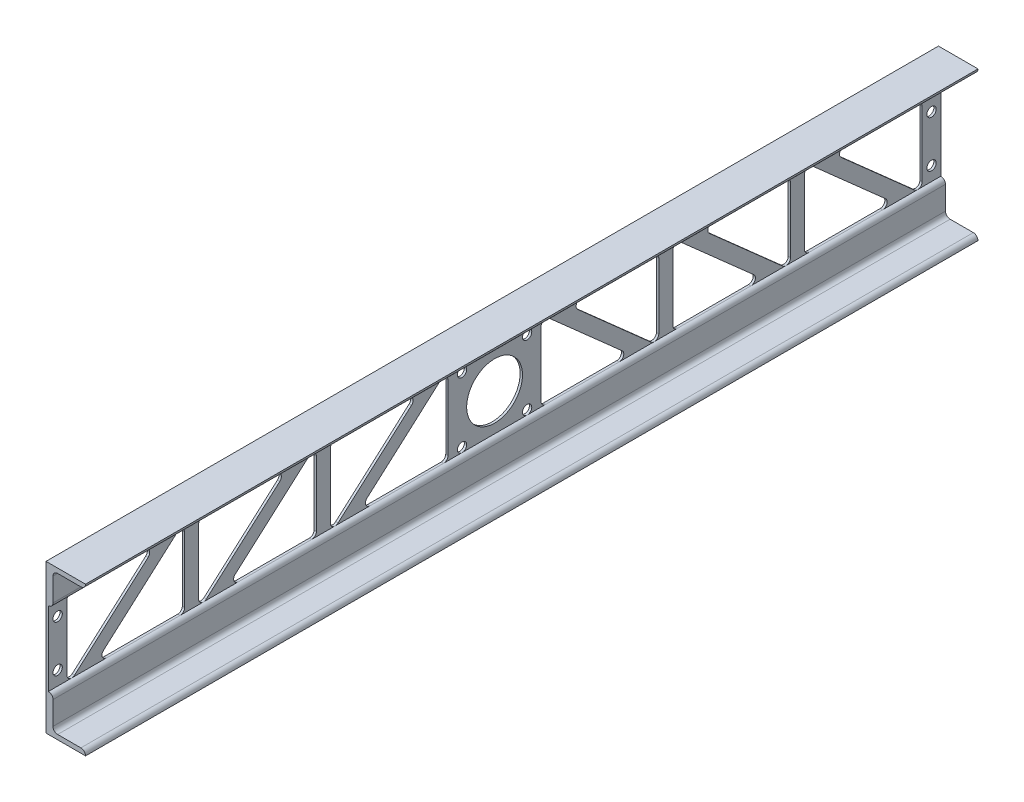
SolidWorks part; units mm, degrees
material "6061 Alloy"
ref_plane "Front Plane" through (0, 0, 0) normal (0, 0, 1) x (1, 0, 0)
ref_plane "Top Plane" through (0, 0, 0) normal (0, 1, 0) x (1, 0, 0)
ref_plane "Right Plane" through (0, 0, 0) normal (1, 0, 0) x (0, 0, -1)
sketch "Sketch1" plane through (0, 0, 0) normal (0, 0, 1) x (1, 0, 0)
  line L1 (0, 0) -> (1.6002, 0)
  line L2 (0, 0) -> (0, 101.6)
  line L3 (0, 101.6) -> (1.6002, 101.6)
  line L4 (1.6002, 0) -> (1.6002, 101.6)
  dimension "D1" = 101.6
  dimension "D2" = 1.6002
extrude "Boss-Extrude1" add sketch "Sketch1" along normal mid plane 609.6
sketch "Sketch2" plane through (0, 0, 0) normal (0, 0, 1) x (1, 0, 0)
  line L0 (27.0002, 101.6) -> (1.6002, 101.6)
  line L1 (1.6002, 101.6) -> (1.6002, 76.2)
  line L2 (4.7752, 79.375) -> (4.7752, 95.25)
  line L3 (7.9502, 98.425) -> (23.8252, 98.425)
  line L4 (1.6002, 50.8) -> (27.0002, 50.8) construction
  line L5 (1.6002, 0) -> (1.6002, 101.6) construction
  line L6 (7.9502, 3.175) -> (23.8252, 3.175)
  line L7 (4.7752, 22.225) -> (4.7752, 6.35)
  line L8 (1.6002, 0) -> (1.6002, 25.4)
  line L9 (27.0002, 0) -> (1.6002, 0)
  arc A0 (1.6002, 76.2) -> (4.7752, 79.375) centre (1.6002, 79.375) ccw
  arc A1 (27.0002, 101.6) -> (23.8252, 98.425) centre (23.8252, 101.6) cw
  arc A2 (4.7752, 95.25) -> (7.9502, 98.425) centre (7.9502, 95.25) cw
  arc A3 (4.7752, 6.35) -> (7.9502, 3.175) centre (7.9502, 6.35) ccw
  arc A4 (27.0002, 0) -> (23.8252, 3.175) centre (23.8252, 0) ccw
  arc A5 (1.6002, 25.4) -> (4.7752, 22.225) centre (1.6002, 22.225) cw
  dimension "D1" = 3.175
  dimension "D2" = 25.4
extrude "Boss-Extrude2" add sketch "Sketch2" along normal mid plane 609.6
sketch "Sketch3" plane through (1.6002, 0, 0) normal (1, 0, 0) x (0, 0, -1)
  line L0 (0, 25.4) -> (0, 76.2) construction
  line L1 (-304.8, 25.4) -> (304.8, 25.4) construction
  line L2 (-304.8, 76.2) -> (304.8, 76.2) construction
  line L3 (-292.1, 73.025) -> (-292.1, 28.575)
  line L4 (-288.925, 76.2) -> (-238.7751, 76.2)
  line L5 (-236.6691, 70.649) -> (-286.819, 26.199)
  line L6 (-304.8, 25.4) -> (-304.8, 76.2) construction
  line L7 (-264.9916, 25.4) -> (-214.8417, 25.4)
  line L8 (-211.6667, 28.575) -> (-211.6667, 73.025)
  line L9 (-216.9476, 75.401) -> (-267.0976, 30.951)
  line L10 (-261.7441, 48.424) -> (-255.4261, 41.2959) construction
  line L11 (-211.6667, 50.8) -> (-202.1417, 50.8) construction
  line L12 (-202.1417, 73.025) -> (-202.1417, 28.575)
  line L13 (-198.9667, 76.2) -> (-148.8167, 76.2)
  line L14 (-146.7108, 70.649) -> (-196.8607, 26.199)
  line L15 (-126.9893, 75.401) -> (-177.1392, 30.951)
  line L16 (-121.7083, 28.575) -> (-121.7083, 73.025)
  line L17 (-175.0333, 25.4) -> (-124.8833, 25.4)
  line L18 (-171.7857, 48.424) -> (-165.4678, 41.2959) construction
  line L19 (-121.7083, 50.8) -> (-112.1833, 50.8) construction
  line L20 (-112.1833, 73.025) -> (-112.1833, 28.575)
  line L21 (-109.0083, 76.2) -> (-58.8584, 76.2)
  line L22 (-56.7524, 70.649) -> (-106.9024, 26.199)
  line L23 (-37.031, 75.401) -> (-87.1809, 30.951)
  line L24 (-31.75, 28.575) -> (-31.75, 73.025)
  line L25 (-85.0749, 25.4) -> (-34.925, 25.4)
  line L26 (-81.8274, 48.424) -> (-75.5095, 41.2959) construction
  line L27 (0, 50.8) -> (-31.75, 50.8) construction
  line L28 (-31.75, 50.8) -> (-22.225, 50.8) construction
  line L29 (81.8274, 48.424) -> (75.5095, 41.2959) construction
  line L30 (121.7083, 50.8) -> (112.1833, 50.8) construction
  line L31 (171.7857, 48.424) -> (165.4678, 41.2959) construction
  line L32 (211.6667, 50.8) -> (202.1417, 50.8) construction
  line L33 (261.7441, 48.424) -> (255.4261, 41.2959) construction
  line L34 (85.0749, 25.4) -> (34.925, 25.4)
  line L35 (31.75, 28.575) -> (31.75, 73.025)
  line L36 (37.031, 75.401) -> (87.1809, 30.951)
  line L37 (56.7524, 70.649) -> (106.9024, 26.199)
  line L38 (109.0083, 76.2) -> (58.8584, 76.2)
  line L39 (112.1833, 73.025) -> (112.1833, 28.575)
  line L40 (175.0333, 25.4) -> (124.8833, 25.4)
  line L41 (121.7083, 28.575) -> (121.7083, 73.025)
  line L42 (126.9893, 75.401) -> (177.1392, 30.951)
  line L43 (146.7108, 70.649) -> (196.8607, 26.199)
  line L44 (198.9667, 76.2) -> (148.8167, 76.2)
  line L45 (202.1417, 73.025) -> (202.1417, 28.575)
  line L46 (216.9476, 75.401) -> (267.0976, 30.951)
  line L47 (211.6667, 28.575) -> (211.6667, 73.025)
  line L48 (264.9916, 25.4) -> (214.8417, 25.4)
  line L49 (236.6691, 70.649) -> (286.819, 26.199)
  line L50 (288.925, 76.2) -> (238.7751, 76.2)
  line L51 (292.1, 73.025) -> (292.1, 28.575)
  circle A0 centre (0, 50.8) radius 19.05
  arc A1 (-292.1, 28.575) -> (-286.819, 26.199) centre (-288.925, 28.575) ccw
  arc A2 (-238.7751, 76.2) -> (-236.6691, 70.649) centre (-238.7751, 73.025) cw
  arc A3 (-292.1, 73.025) -> (-288.925, 76.2) centre (-288.925, 73.025) cw
  arc A4 (-264.9916, 25.4) -> (-267.0976, 30.951) centre (-264.9916, 28.575) cw
  arc A5 (-214.8417, 25.4) -> (-211.6667, 28.575) centre (-214.8417, 28.575) ccw
  arc A6 (-211.6667, 73.025) -> (-216.9476, 75.401) centre (-214.8417, 73.025) ccw
  arc A7 (-202.1417, 73.025) -> (-198.9667, 76.2) centre (-198.9667, 73.025) cw
  arc A8 (-148.8167, 76.2) -> (-146.7108, 70.649) centre (-148.8167, 73.025) cw
  arc A9 (-202.1417, 28.575) -> (-196.8607, 26.199) centre (-198.9667, 28.575) ccw
  arc A10 (-175.0333, 25.4) -> (-177.1392, 30.951) centre (-175.0333, 28.575) cw
  arc A11 (-121.7083, 73.025) -> (-126.9893, 75.401) centre (-124.8833, 73.025) ccw
  arc A12 (-124.8833, 25.4) -> (-121.7083, 28.575) centre (-124.8833, 28.575) ccw
  arc A13 (-112.1833, 73.025) -> (-109.0083, 76.2) centre (-109.0083, 73.025) cw
  arc A14 (-58.8584, 76.2) -> (-56.7524, 70.649) centre (-58.8584, 73.025) cw
  arc A15 (-112.1833, 28.575) -> (-106.9024, 26.199) centre (-109.0083, 28.575) ccw
  arc A16 (-85.0749, 25.4) -> (-87.1809, 30.951) centre (-85.0749, 28.575) cw
  arc A17 (-31.75, 73.025) -> (-37.031, 75.401) centre (-34.925, 73.025) ccw
  arc A18 (-34.925, 25.4) -> (-31.75, 28.575) centre (-34.925, 28.575) ccw
  arc A19 (34.925, 25.4) -> (31.75, 28.575) centre (34.925, 28.575) cw
  arc A20 (31.75, 73.025) -> (37.031, 75.401) centre (34.925, 73.025) cw
  arc A21 (85.0749, 25.4) -> (87.1809, 30.951) centre (85.0749, 28.575) ccw
  arc A22 (112.1833, 28.575) -> (106.9024, 26.199) centre (109.0083, 28.575) cw
  arc A23 (58.8584, 76.2) -> (56.7524, 70.649) centre (58.8584, 73.025) ccw
  arc A24 (112.1833, 73.025) -> (109.0083, 76.2) centre (109.0083, 73.025) ccw
  arc A25 (124.8833, 25.4) -> (121.7083, 28.575) centre (124.8833, 28.575) cw
  arc A26 (121.7083, 73.025) -> (126.9893, 75.401) centre (124.8833, 73.025) cw
  arc A27 (175.0333, 25.4) -> (177.1392, 30.951) centre (175.0333, 28.575) ccw
  arc A28 (202.1417, 28.575) -> (196.8607, 26.199) centre (198.9667, 28.575) cw
  arc A29 (148.8167, 76.2) -> (146.7108, 70.649) centre (148.8167, 73.025) ccw
  arc A30 (202.1417, 73.025) -> (198.9667, 76.2) centre (198.9667, 73.025) ccw
  arc A31 (211.6667, 73.025) -> (216.9476, 75.401) centre (214.8417, 73.025) cw
  arc A32 (214.8417, 25.4) -> (211.6667, 28.575) centre (214.8417, 28.575) cw
  arc A33 (264.9916, 25.4) -> (267.0976, 30.951) centre (264.9916, 28.575) ccw
  arc A34 (292.1, 73.025) -> (288.925, 76.2) centre (288.925, 73.025) ccw
  arc A35 (238.7751, 76.2) -> (236.6691, 70.649) centre (238.7751, 73.025) ccw
  arc A36 (292.1, 28.575) -> (286.819, 26.199) centre (288.925, 28.575) cw
  point P16 (-230.4063, 76.2)
  point P19 (-292.1, 76.2)
  point P20 (-288.925, 25.4)
  point P28 (-273.3604, 25.4)
  point P31 (-211.6667, 25.4)
  point P34 (-214.8417, 76.2)
  point P148 (214.8417, 76.2)
  point P149 (211.6667, 25.4)
  point P150 (273.3604, 25.4)
  point P151 (288.925, 25.4)
  point P152 (292.1, 76.2)
  point P153 (230.4063, 76.2)
  dimension "D1" = 38.1
  dimension "D2" = 3.175
  dimension "D4" = 3.175
  dimension "D3" = 12.7
  dimension "D6" = 9.525
  dimension "D7" = 31.75
  dimension "D5" = 3
extrude "Cut-Extrude1" cut sketch "Sketch3" against normal through all
sketch "Sketch4" plane through (1.6002, 0, 0) normal (1, 0, 0) x (0, 0, -1)
  line L1 (-22.225, 28.575) -> (22.225, 28.575) construction
  line L2 (-22.225, 28.575) -> (-22.225, 73.025) construction
  line L3 (-22.225, 73.025) -> (22.225, 73.025) construction
  line L4 (22.225, 28.575) -> (22.225, 73.025) construction
  line L5 (-22.225, 28.575) -> (22.225, 73.025) construction
  line L6 (-22.225, 73.025) -> (22.225, 28.575) construction
  circle A0 centre (-22.225, 73.025) radius 3.175
  circle A1 centre (22.225, 73.025) radius 3.175
  circle A2 centre (22.225, 28.575) radius 3.175
  circle A3 centre (-22.225, 28.575) radius 3.175
  point P0 (0, 50.8)
  dimension "D2" = 6.35
  dimension "D1" = 44.45
extrude "Cut-Extrude2" cut sketch "Sketch4" against normal through all
sketch "Sketch5" plane through (1.6002, 0, 0) normal (1, 0, 0) x (0, 0, -1)
  line L0 (-304.8, 50.8) -> (-292.1, 50.8) construction
  line L1 (-304.8, 25.4) -> (-304.8, 76.2) construction
  line L2 (-292.1, 73.025) -> (-292.1, 28.575) construction
  line L3 (-298.45, 66.675) -> (-298.45, 34.925) construction
  line L4 (0, 76.2) -> (0, 25.4) construction
  line L5 (-22.225, 76.2) -> (22.225, 76.2) construction
  line L6 (-22.225, 25.4) -> (22.225, 25.4) construction
  line L7 (298.45, 66.675) -> (298.45, 34.925) construction
  line L8 (304.8, 50.8) -> (292.1, 50.8) construction
  circle A0 centre (-298.45, 66.675) radius 3.175
  circle A1 centre (-298.45, 34.925) radius 3.175
  circle A2 centre (298.45, 34.925) radius 3.175
  circle A3 centre (298.45, 66.675) radius 3.175
  point P8 (-298.45, 50.8)
  point P23 (298.45, 50.8)
  dimension "D2" = 6.35
  dimension "D1" = 31.75
extrude "Cut-Extrude3" cut sketch "Sketch5" against normal through all
